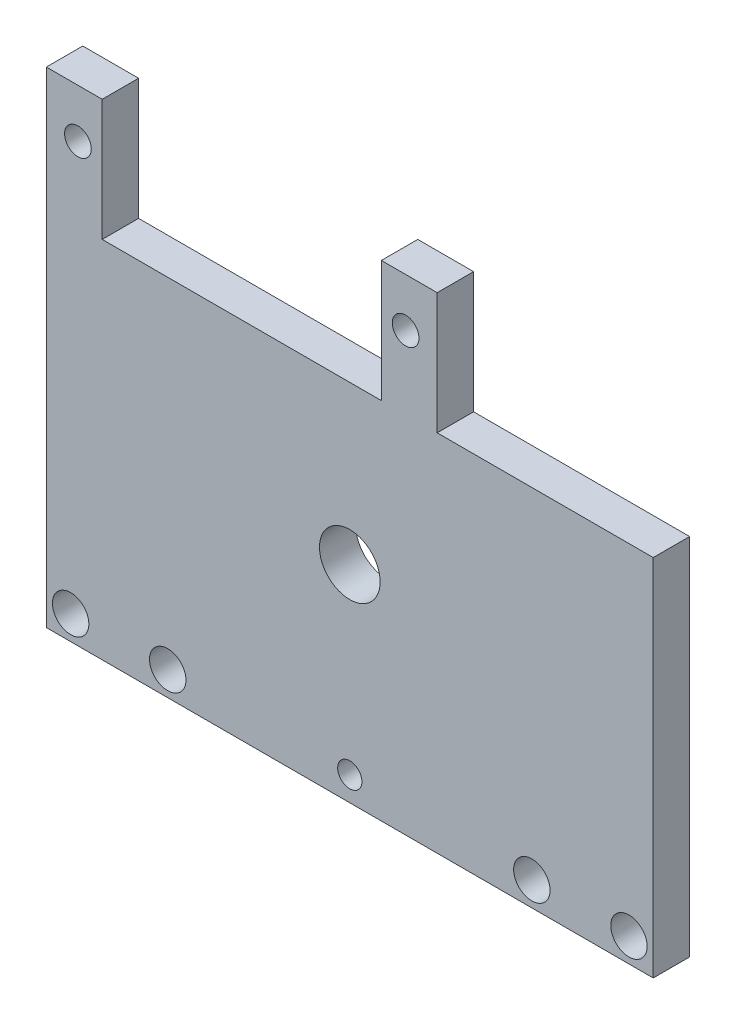
SolidWorks part; units mm, degrees
ref_plane "Front" through (0, 0, 0) normal (0, 0, 1) x (1, 0, 0)
ref_plane "Top" through (0, 0, 0) normal (0, 1, 0) x (1, 0, 0)
ref_plane "Right" through (0, 0, 0) normal (1, 0, 0) x (0, 0, -1)
sketch "Эскиз1" plane through (0, 0, 0) normal (0, 0, 1) x (1, 0, 0)
  line L0 (-12.4103, 7.3513) -> (-12.4103, -5.6487) construction
  line L2 (-37.4103, -22.6487) -> (12.5897, -22.6487)
  line L3 (-37.4103, -22.6487) -> (-37.4103, 7.3513)
  line L4 (-32.8103, 7.3513) -> (-9.8103, 7.3513)
  line L5 (12.5897, -22.6487) -> (12.5897, 7.3513)
  line L6 (-12.4103, -22.6487) -> (-12.4103, -5.6487) construction
  line L8 (-37.4103, 7.3513) -> (-37.4103, 17.3513)
  line L9 (-37.4103, 17.3513) -> (-32.8103, 17.3513)
  line L10 (-32.8103, 7.3513) -> (-32.8103, 17.3513)
  line L11 (-5.2103, 7.3513) -> (12.5897, 7.3513)
  line L13 (-9.8103, 7.3513) -> (-9.8103, 17.3513)
  line L14 (-9.8103, 17.3513) -> (-5.2103, 17.3513)
  line L15 (-5.2103, 7.3513) -> (-5.2103, 17.3513)
  circle A0 centre (-12.4103, -5.6487) radius 2.5
  circle A1 centre (-34.8103, 13.3513) radius 1.1
  circle A2 centre (-7.8103, 13.3513) radius 1.1
  circle A3 centre (-35.4103, -20.6487) radius 1.5
  circle A4 centre (10.5897, -20.6487) radius 1.5
  circle A6 centre (-12.4103, -20.6487) radius 1
  circle A7 centre (-27.4103, -20.6487) radius 1.5
  circle A8 centre (2.5897, -20.6487) radius 1.5
  dimension "D3" = 5
  dimension "D5" = 4.6
  dimension "D2" = 50
  dimension "D7" = 4
  dimension "D9" = 23
  dimension "D13" = 2
  dimension "D15" = 2
  dimension "D17" = 2
  dimension "D18" = 8
  dimension "D19" = 8
  dimension "D4" = 13
  dimension "D6" = 10
  dimension "D8" = 4.6
  dimension "D10" = 2
  dimension "D11" = 2
  dimension "D12" = 30
  dimension "D14" = 2
  dimension "D16" = 2
extrude "Бобышка-Вытянуть1" add sketch "Эскиз1" along normal blind 3
